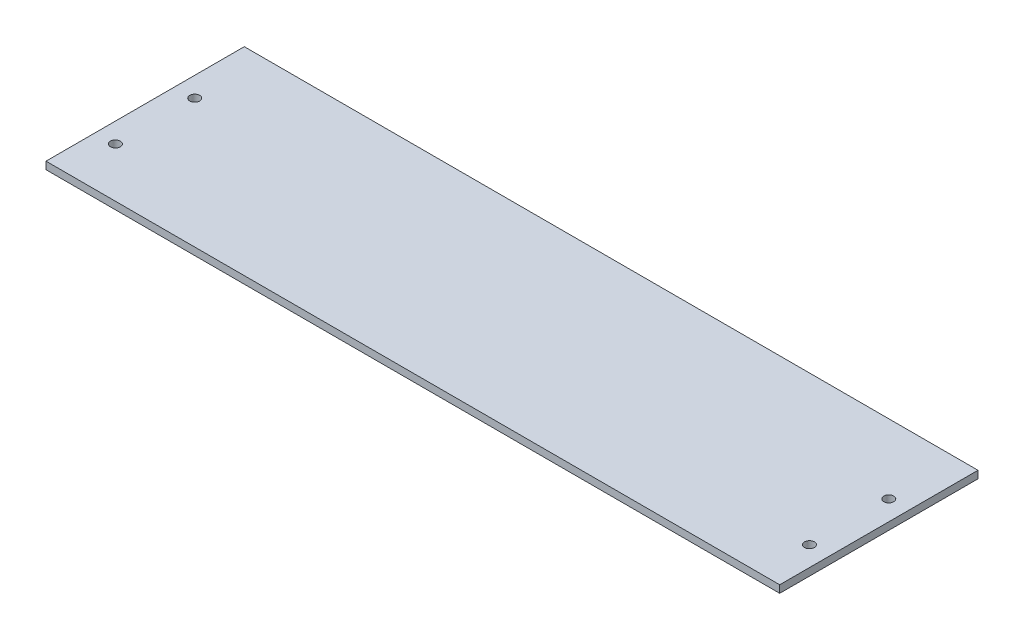
SolidWorks part; units mm, degrees
material "ABS PC"
ref_plane "Front Plane" through (0, 0, 0) normal (0, 0, 1) x (1, 0, 0)
ref_plane "Top Plane" through (0, 0, 0) normal (0, 1, 0) x (1, 0, 0)
ref_plane "Right Plane" through (0, 0, 0) normal (1, 0, 0) x (0, 0, -1)
sketch "Sketch1" plane through (0, 0, 0) normal (0, 1, 0) x (1, 0, 0)
  line L0 (-148, 80) -> (-148, 0) construction
  line L1 (0, 0) -> (-296, 0)
  line L2 (0, 0) -> (0, 80)
  line L3 (0, 80) -> (-296, 80)
  line L4 (-296, 0) -> (-296, 80)
  circle A0 centre (-8, 20) radius 2
  circle A1 centre (-8, 52) radius 2
  circle A2 centre (-288, 52) radius 2
  circle A3 centre (-288, 20) radius 2
  dimension "D1" = 4
  dimension "D2" = 32
  dimension "D3" = 20
  dimension "D4" = 8
  dimension "D5" = 80
  dimension "D6" = 296
extrude "Boss-Extrude1" add sketch "Sketch1" along normal blind 3
